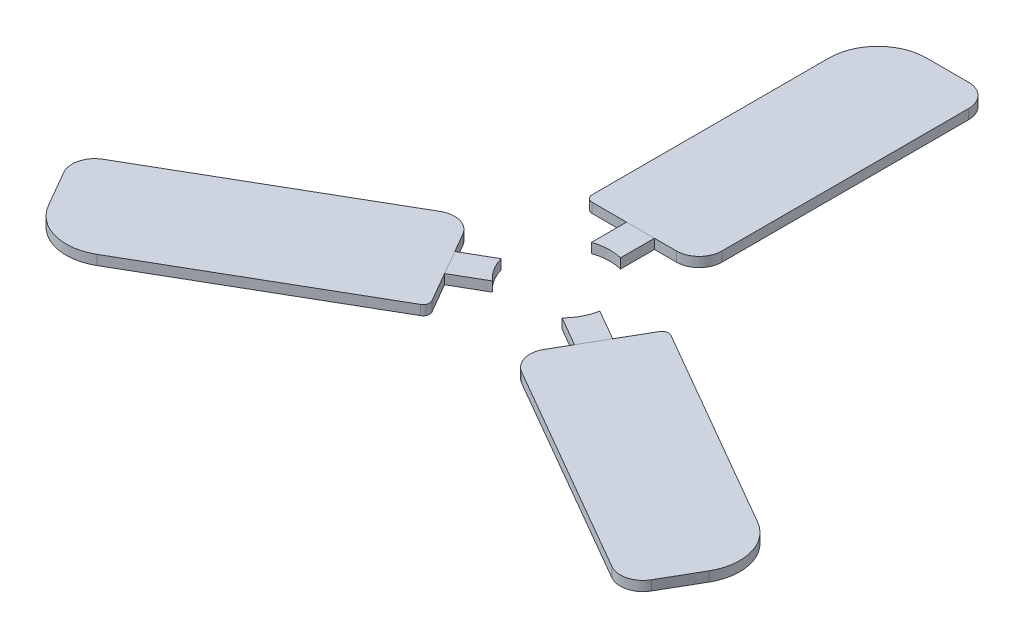
SolidWorks part; units mm, degrees
ref_plane "Front Plane" through (0, 0, 0) normal (0, 0, 1) x (1, 0, 0)
ref_plane "Top Plane" through (0, 0, 0) normal (0, 1, 0) x (1, 0, 0)
ref_plane "Right Plane" through (0, 0, 0) normal (1, 0, 0) x (0, 0, -1)
sketch "Sketch1" plane through (0, 0, 0) normal (0, 1, 0) x (1, 0, 0)
  line L0 (0, 0) -> (-105.994, 0)
  line L1 (-125.994, 20) -> (-125.994, 750)
  line L2 (24.006, 900) -> (154.006, 900)
  line L3 (224.006, 830) -> (224.006, 70)
  line L4 (154.006, 0) -> (0, 0)
  arc A0 (-125.994, 750) -> (24.006, 900) centre (24.006, 750) cw
  arc A1 (224.006, 70) -> (154.006, 0) centre (154.006, 70) cw
  arc A2 (154.006, 900) -> (224.006, 830) centre (154.006, 830) cw
  arc A3 (-105.994, 0) -> (-125.994, 20) centre (-105.994, 20) cw
  point P8 (-125.994, 900)
  point P13 (224.006, 900)
  point P16 (-125.994, 0)
  dimension "D3" = 150
  dimension "D4" = 70
  dimension "D5" = 20
  dimension "D1" = 900
  dimension "D2" = 350
sketch "Sketch2" plane through (0, 0, 0) normal (0, 1, 0) x (1, 0, 0)
  line L3 (49.006, -99.7994) -> (49.006, -100)
  circle A0 centre (49.006, -250) radius 150.2006
  dimension "D1" = 150
extrude "Boss-Extrude1" add sketch "Sketch1" along normal blind 30
extrude "Boss-Extrude2" add sketch "Sketch2" along normal blind 30 contours A0
pattern_circular "CirPattern2" count 3 over 360 about axis through (49.006, 0, 250) along (0, 1, 0) of "Boss-Extrude1"
sketch "Sketch3" plane through (0, 30, 0) normal (0, 1, 0) x (1, 0, 0)
  line L0 (0, -108.0189) -> (0, 0)
  line L1 (0, 0) -> (86.0738, 0)
  line L2 (-105.994, 0) -> (154.006, 0) construction
  line L3 (86.0738, 0) -> (86.0738, -104.4453)
  circle A0 centre (49.006, -250) radius 150.2006 construction
  circle A2 centre (49.006, -250) radius 150.2006
  arc A3 (86.0738, -104.4453) -> (0, -108.0189) centre (49.006, -250) ccw
  dimension "D1" = 0
extrude "Boss-Extrude4" add sketch "Sketch3" against normal blind 30 separate body
pattern_circular "CirPattern3" count 3 over 360 about axis through (49.006, 0, 250) along (0, 1, 0) of bodies 107
sketch "Sketch4" plane through (0, 30, 0) normal (0, 1, 0) x (1, 0, 0)
  circle A1 centre (49.006, -250) radius 150.2006
  circle A2 centre (49.006, -250) radius 150.2006
  dimension "D1" = 0
extrude "Cut-Extrude1" cut sketch "Sketch4" against normal blind 30
